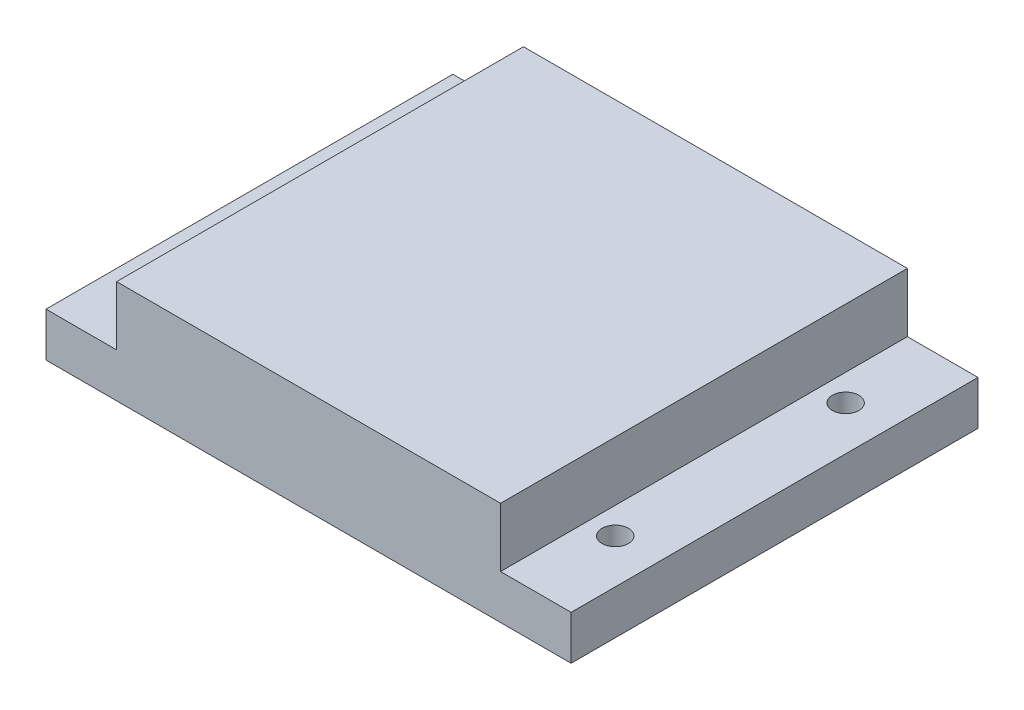
SolidWorks part; units mm, degrees
ref_plane "前视基准面" through (0, 0, 0) normal (0, 0, 1) x (1, 0, 0)
ref_plane "上视基准面" through (0, 0, 0) normal (0, 1, 0) x (1, 0, 0)
ref_plane "右视基准面" through (0, 0, 0) normal (1, 0, 0) x (0, 0, -1)
sketch "草图1" plane through (0, 0, 0) normal (0, 0, 1) x (1, 0, 0)
  line L0 (0, 0) -> (0, 5)
  line L1 (0, 0) -> (59.5, 0)
  line L5 (59.5, 0) -> (59.5, 5)
  line L6 (59.5, 5) -> (51.5, 5)
  line L7 (0, 5) -> (8, 5)
  line L8 (8, 5) -> (8, 11.7)
  line L9 (8, 11.7) -> (51.5, 11.7)
  line L10 (51.5, 11.7) -> (51.5, 5)
extrude "凸台-拉伸1" add sketch "草图1" along normal blind 46.1
sketch "草图2" plane through (0, 0, 0) normal (0, -1, 0) x (1, 0, 0)
  circle A2 centre (5, 36.1) radius 1.5
  circle A3 centre (5, 10) radius 1.5
  circle A4 centre (54.5, 36.1) radius 1.5
  circle A5 centre (54.5, 10) radius 1.5
extrude "切除-拉伸1" cut sketch "草图2" against normal through all
